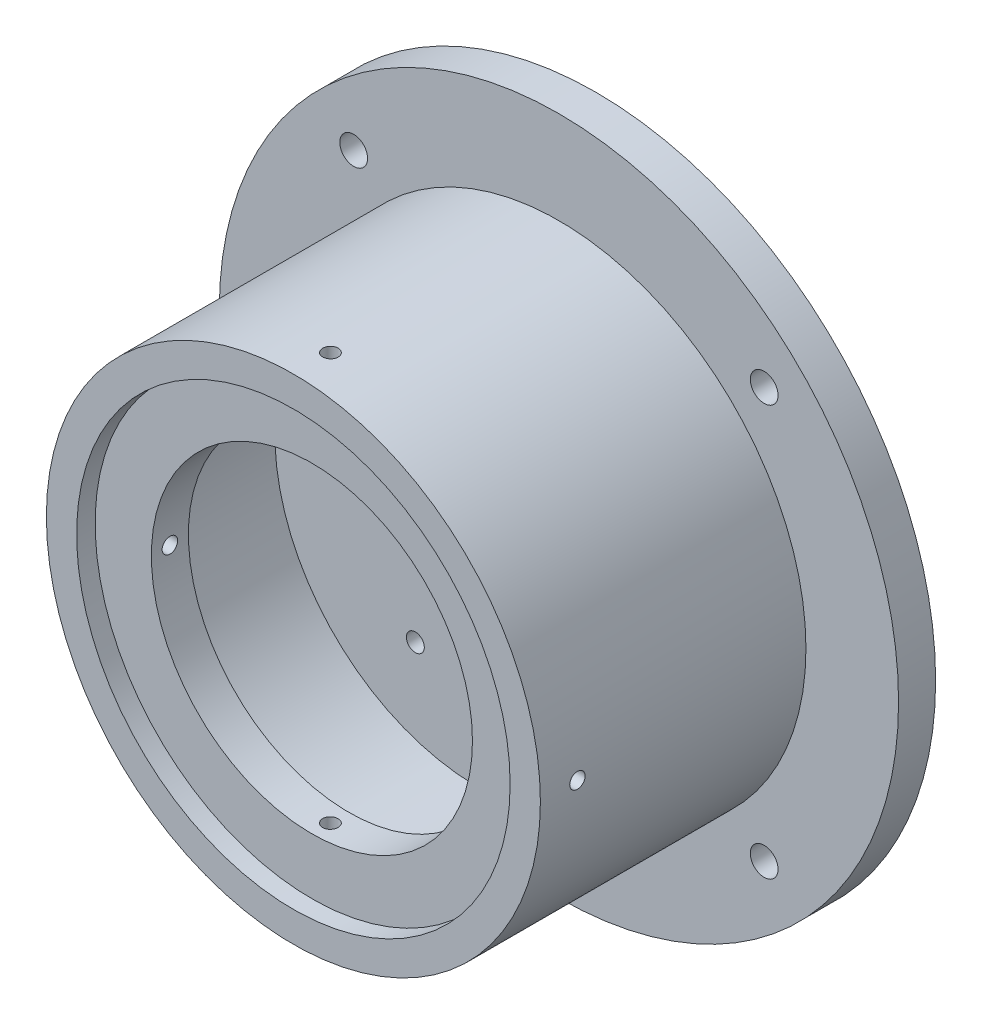
SolidWorks part; units mm, degrees
material "Aleación 6061"
ref_plane "Alzado" through (0, 0, 0) normal (0, 0, 1) x (1, 0, 0)
ref_plane "Planta" through (0, 0, 0) normal (0, 1, 0) x (1, 0, 0)
ref_plane "Vista lateral" through (0, 0, 0) normal (1, 0, 0) x (0, 0, -1)
sketch "Sk_Brida" plane through (0, 0, 0) normal (0, 0, 1) x (1, 0, 0)
  circle A0 centre (0, 0) radius 55
  dimension "D1" = 110
extrude "Brida" add sketch "Sk_Brida" along normal blind 6 from offset 10
sketch "Sk_Tubo" plane through (0, 0, 0) normal (0, 0, 1) x (1, 0, 0)
  circle A0 centre (0, 0) radius 40
  circle A1 centre (0, 0) radius 33
  dimension "D1" = 80
  dimension "D2" = 66
extrude "Tubo" add sketch "Sk_Tubo" along normal blind 34 from offset 16
sketch "Sk_Aro_rodamiento" plane through (0, 0, 0) normal (0, 0, 1) x (1, 0, 0)
  circle A0 centre (0, 0) radius 40
  circle A1 centre (0, 0) radius 26
  dimension "D1" = 80
  dimension "D2" = 52
extrude "Aro_rodamiento" add sketch "Sk_Aro_rodamiento" along normal blind 6 from offset 50
sketch "Sk_Asiento_arandela_alojamiento_51110" plane through (0, 0, 0) normal (0, 0, 1) x (1, 0, 0)
  circle A0 centre (0, 0) radius 40
  circle A1 centre (0, 0) radius 35.1
  dimension "D1" = 80
  dimension "D2" = 70.2
extrude "Asiento_arandela_alojamiento_51110" add sketch "Sk_Asiento_arandela_alojamiento_51110" along normal blind 3 from offset 56
sketch "Sk_Placa_motor" plane through (0, 0, 0) normal (0, 0, 1) x (1, 0, 0)
  circle A0 centre (0, 0) radius 33
  dimension "D1" = 66
extrude "Placa_motor" add sketch "Sk_Placa_motor" along normal blind 6 from offset 23
sketch "Sk_Hueco_brida" plane through (0, 0, 0) normal (0, 0, 1) x (1, 0, 0)
  circle A0 centre (0, 0) radius 28
  dimension "D1" = 56
extrude "Hueco_brida" cut sketch "Sk_Hueco_brida" along normal blind 13 from offset 10
sketch "Sk_Centro_motor" plane through (0, 0, 0) normal (0, 0, 1) x (1, 0, 0)
  circle A0 centre (0, 0) radius 8
  dimension "D1" = 16
extrude "Centro_motor" cut sketch "Sk_Centro_motor" along normal blind 6 from offset 23
sketch "Sk_Pasantes_M2-5_motor" plane through (0, 0, 0) normal (0, 0, 1) x (1, 0, 0)
  circle A0 centre (20.5, 0) radius 1.45
  circle A1 centre (10.25, 17.7535) radius 1.45
  circle A2 centre (-10.25, 17.7535) radius 1.45
  circle A3 centre (-20.5, 0) radius 1.45
  circle A4 centre (-10.25, -17.7535) radius 1.45
  circle A5 centre (10.25, -17.7535) radius 1.45
  dimension "D1" = 2.9
  dimension "D3" = 2.9
  dimension "D6" = 2.9
  dimension "D9" = 2.9
  dimension "D11" = 2.9
  dimension "D14" = 2.9
  dimension "D2" = 20.5
  dimension "D4" = 10.25
  dimension "D5" = 17.7535
  dimension "D7" = 10.25
  dimension "D8" = 17.7535
  dimension "D10" = 20.5
  dimension "D12" = 10.25
  dimension "D13" = 17.7535
  dimension "D15" = 10.25
  dimension "D16" = 17.7535
extrude "Pasantes_M2-5_motor" cut sketch "Sk_Pasantes_M2-5_motor" along normal blind 6 from offset 23
sketch "Sk_Pasantes_M4_brida" plane through (0, 0, 0) normal (0, 0, 1) x (1, 0, 0)
  circle A0 centre (33.234, 33.234) radius 2.25
  circle A1 centre (-33.234, 33.234) radius 2.25
  circle A2 centre (-33.234, -33.234) radius 2.25
  circle A3 centre (33.234, -33.234) radius 2.25
  dimension "D1" = 4.5
  dimension "D4" = 4.5
  dimension "D7" = 4.5
  dimension "D10" = 4.5
  dimension "D2" = 33.234
  dimension "D3" = 33.234
  dimension "D5" = 33.234
  dimension "D6" = 33.234
  dimension "D8" = 33.234
  dimension "D9" = 33.234
  dimension "D11" = 33.234
  dimension "D12" = 33.234
extrude "Pasantes_M4_brida" cut sketch "Sk_Pasantes_M4_brida" along normal blind 6 from offset 10
sketch "Croquis1" plane through (0, 0, 0) normal (0, 1, 0) x (1, 0, 0)
  circle A0 centre (0, -53) radius 1.25
extrude "Rosca_M3_cubierta_A" cut sketch "Croquis1" against normal through all and the other way through all
sketch "Croquis2" plane through (0, 0, 0) normal (1, 0, 0) x (0, 0, -1)
  circle A0 centre (-53, 0) radius 1.25
extrude "Rosca_M3_cubierta_B" cut sketch "Croquis2" against normal through all and the other way through all
